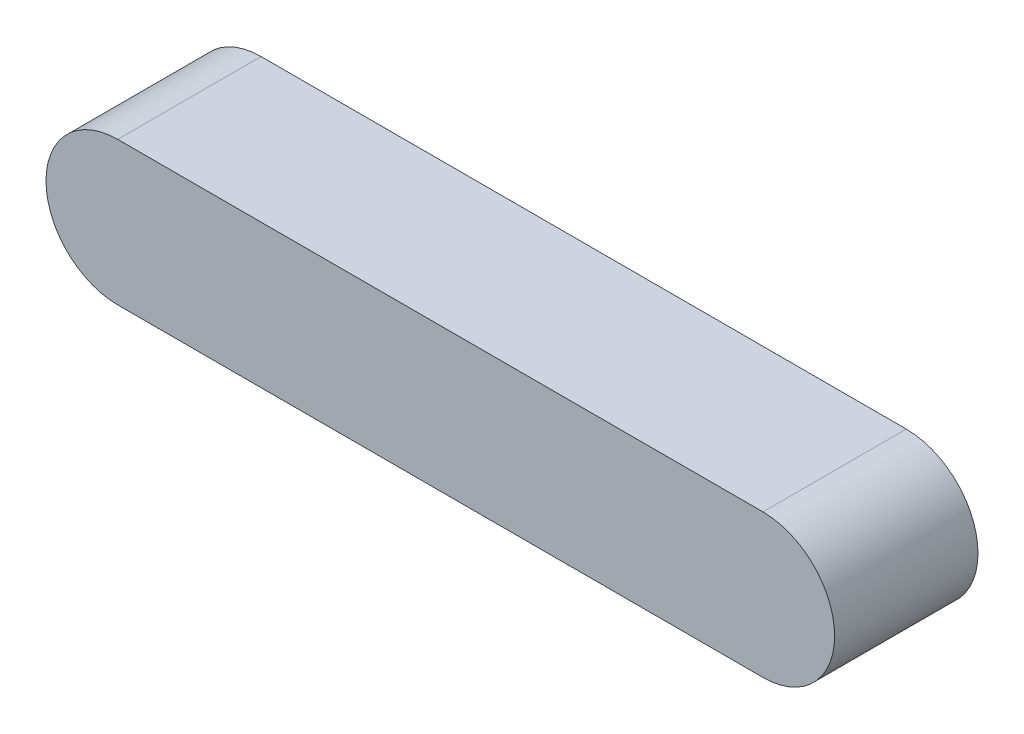
SolidWorks part; units mm, degrees
ref_plane "Front Plane" through (0, 0, 0) normal (0, 0, 1) x (1, 0, 0)
ref_plane "Top Plane" through (0, 0, 0) normal (0, 1, 0) x (1, 0, 0)
ref_plane "Right Plane" through (0, 0, 0) normal (1, 0, 0) x (0, 0, -1)
sketch "Sketch1" plane through (0, 0, 0) normal (0, 0, 1) x (1, 0, 0)
  line L0 (0, 0) -> (18, 0) construction
  line L1 (0, 2) -> (18, 2)
  line L2 (0, -2) -> (18, -2)
  arc A0 (0, 2) -> (0, -2) centre (0, 0) ccw
  arc A1 (18, -2) -> (18, 2) centre (18, 0) ccw
  point P3 (9, 0)
  dimension "D1" = 4
  dimension "D2" = 18
extrude "Boss-Extrude1" add sketch "Sketch1" along normal blind 4
